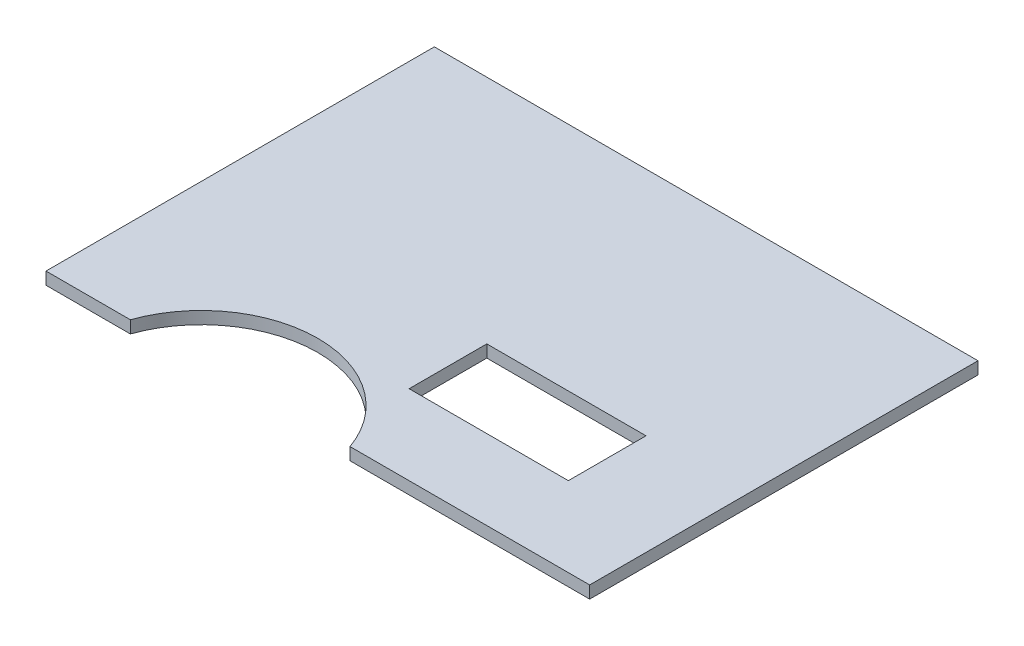
SolidWorks part; units mm, degrees
material "Oak"
ref_plane "Front Plane" through (0, 0, 0) normal (0, 0, 1) x (1, 0, 0)
ref_plane "Top Plane" through (0, 0, 0) normal (0, 1, 0) x (1, 0, 0)
ref_plane "Right Plane" through (0, 0, 0) normal (1, 0, 0) x (0, 0, -1)
sketch "Sketch1" plane through (0, 0, 0) normal (0, 1, 0) x (1, 0, 0)
  line L1 (0, 0) -> (140, 0)
  line L2 (0, 0) -> (0, 100)
  line L3 (0, 100) -> (140, 100)
  line L4 (140, 0) -> (140, 100)
  dimension "D1" = 140
  dimension "D2" = 100
extrude "Boss-Extrude1" add sketch "Sketch1" along normal blind 3.175
sketch "Sketch2" plane through (0, 3.175, 0) normal (0, 1, 0) x (1, 0, 0)
  line L0 (140, 0) -> (140, 100) construction
  line L1 (0, 0) -> (140, 0) construction
  line L3 (73, 40.51) -> (114, 40.51)
  line L4 (73, 40.51) -> (73, 20.51)
  line L5 (73, 20.51) -> (114, 20.51)
  line L6 (114, 40.51) -> (114, 20.51)
  point P0 (103.75, 30.51)
  dimension "D1" = 36.25
  dimension "D2" = 30.51
  dimension "D3" = 41
  dimension "D4" = 20
  dimension "D5" = 10
  dimension "D6" = 30.75
extrude "Cut-Extrude1" cut sketch "Sketch2" against normal blind 10
sketch "Sketch3" plane through (0, 3.175, 0) normal (0, 1, 0) x (1, 0, 0)
  line L0 (0, 0) -> (140, 0) construction
  line L1 (0, 100) -> (0, 0) construction
  circle A0 centre (50, -10) radius 30
  dimension "D1" = 60
  dimension "D2" = 10
  dimension "D3" = 50
extrude "Cut-Extrude2" cut sketch "Sketch3" against normal blind 10
